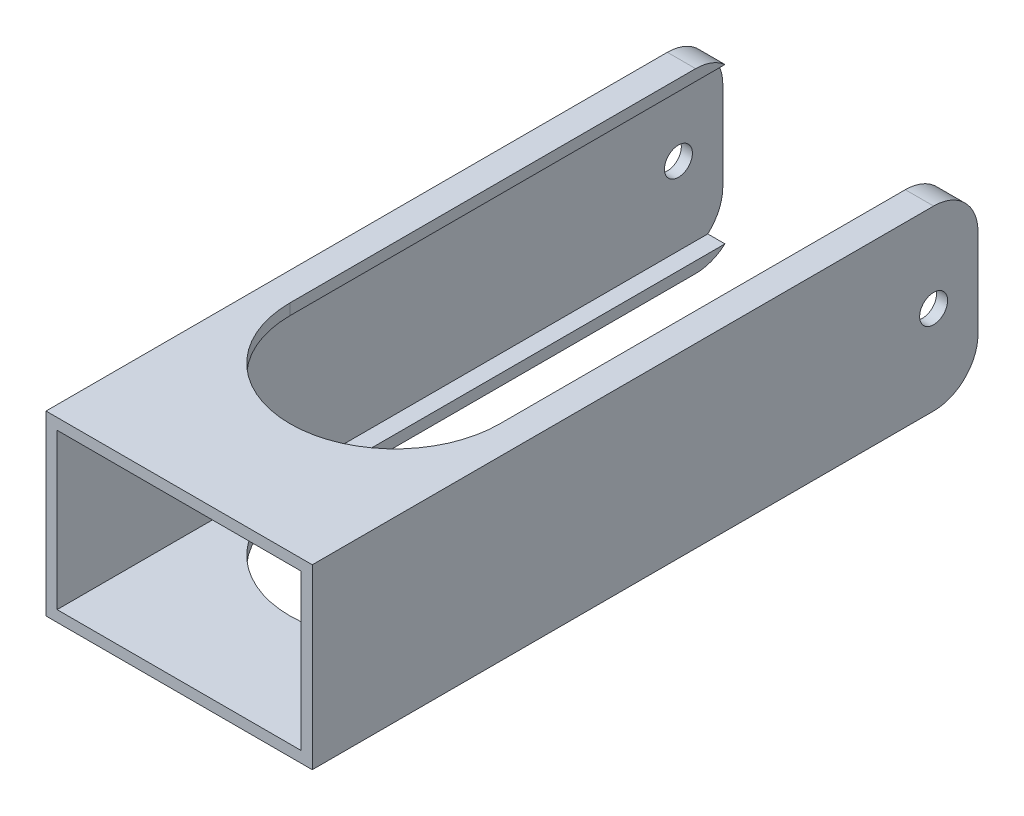
SolidWorks part; units mm, degrees
material "6061 Alloy"
ref_plane "Front Plane" through (0, 0, 0) normal (0, 0, 1) x (1, 0, 0)
ref_plane "Top Plane" through (0, 0, 0) normal (0, 1, 0) x (1, 0, 0)
ref_plane "Right Plane" through (0, 0, 0) normal (1, 0, 0) x (0, 0, -1)
sketch "Sketch1" plane through (0, 0, 0) normal (0, 0, 1) x (1, 0, 0)
  line L0 (38.1, 0) -> (34.925, 0) construction
  line L1 (-38.1, 0) -> (38.1, 0) construction
  line L2 (0, 25.4) -> (0, -25.4)
  point P7 (0, 0)
sketch "Sketch2" plane through (0, 0, 0) normal (1, 0, 0) x (0, 0, -1)
  line L0 (95.25, 0) -> (-95.25, 0)
  point P4 (0, 0)
  dimension "Length" = 190.5
sketch "Sketch3" plane through (0, 0, 0) normal (0, 0, 1) x (1, 0, 0)
  line L0 (-38.1, 0) -> (38.1, 0) construction
  line L5 (38.1, -25.4) -> (-38.1, -25.4)
  line L6 (38.1, -25.4) -> (38.1, 25.4)
  line L11 (38.1, 25.4) -> (-38.1, 25.4)
  line L12 (-38.1, -25.4) -> (-38.1, 25.4)
  line L14 (38.1, -25.4) -> (-38.1, 25.4) construction
  line L15 (38.1, 25.4) -> (-38.1, -25.4) construction
  line L16 (34.925, -22.225) -> (-34.925, -22.225)
  line L17 (34.925, -22.225) -> (34.925, 22.225)
  line L18 (34.925, 22.225) -> (-34.925, 22.225)
  line L19 (-34.925, -22.225) -> (-34.925, 22.225)
  line L20 (34.925, -22.225) -> (-34.925, 22.225) construction
  line L21 (34.925, 22.225) -> (-34.925, -22.225) construction
  point P0 (0, 0)
  point P5 (0, 0)
  point P13 (34.925, -25.4)
  dimension "D1" = 3.175
  dimension "D3" = 76.2
  dimension "D4" = 50.8
  dimension "D2" = 3.175
extrude "Boss-Extrude1" add sketch "Sketch3" along normal up to vertex (95.25 mm away) and the other way up to vertex (95.25 mm away) up to point (0, 0, 95.25) other way up to point (0, 0, -95.25)
sketch "Sketch5" plane through (0, 0, 0) normal (1, 0, 0) x (0, 0, -1)
  line L0 (-95.25, 0) -> (95.25, 0) construction
  line L3 (-95.25, -25.4) -> (-95.25, 25.4) construction
  line L4 (95.25, -25.4) -> (95.25, 25.4) construction
  point P6 (-9.525, 0)
  point P7 (19.05, 0)
  point P8 (-19.05, 0)
  point P10 (9.525, 0)
  dimension "D1" = 85.725
  dimension "D2" = 114.3
  dimension "D3" = 85.725
  dimension "D4" = 114.3
sketch "Sketch6" plane through (0, 25.4, 0) normal (0, 1, 0) x (1, 0, 0)
  line L0 (-30, 95.25) -> (-30, -33.5)
  line L1 (38.1, 95.25) -> (-38.1, 95.25) construction
  line L2 (30, 95.25) -> (30, -33.5)
  line L3 (38.1, -95.25) -> (-38.1, -95.25) construction
  arc A0 (-30, -33.5) -> (30, -33.5) centre (0, -33.5) ccw
  line M4 (38.1, 95.25) -> (-38.1, 95.25)
  dimension "D1" = 31.75
  dimension "D2" = 60
extrude "Cut-Extrude1" cut sketch "Sketch6" against normal through all and the other way through all contours L0 A0 L2 M4
sketch "Sketch7" plane through (38.1, 0, 0) normal (1, 0, 0) x (0, 0, -1)
  line L2 (95.25, -25.4) -> (95.25, 25.4) construction
  circle A0 centre (82.55, 0) radius 4
  dimension "D1" = 8
  dimension "D2" = 12.7
extrude "Cut-Extrude2" cut sketch "Sketch7" against normal through all
fillet "Fillet1" radius 12.7 4 edges at (-34.05, -25.4, -95.25) (-34.05, 25.4, -95.25) (34.05, -25.4, -95.25) (34.05, 25.4, -95.25)
equation "\"D1@Sketch3\"=\"Wall thickness@Sketch1\""
equation "\"D1@Sketch5\"=\"Width@Sketch1\"*1.125"
equation "\"D2@Sketch5\"=\"Width@Sketch1\"*1.5"
equation "\"D3@Sketch5\"=\"D1@Sketch5\""
equation "\"D4@Sketch5\"=\"D2@Sketch5\""
equation "\"D2@Sketch3\"=\"Wall Thickness@Sketch1\""
